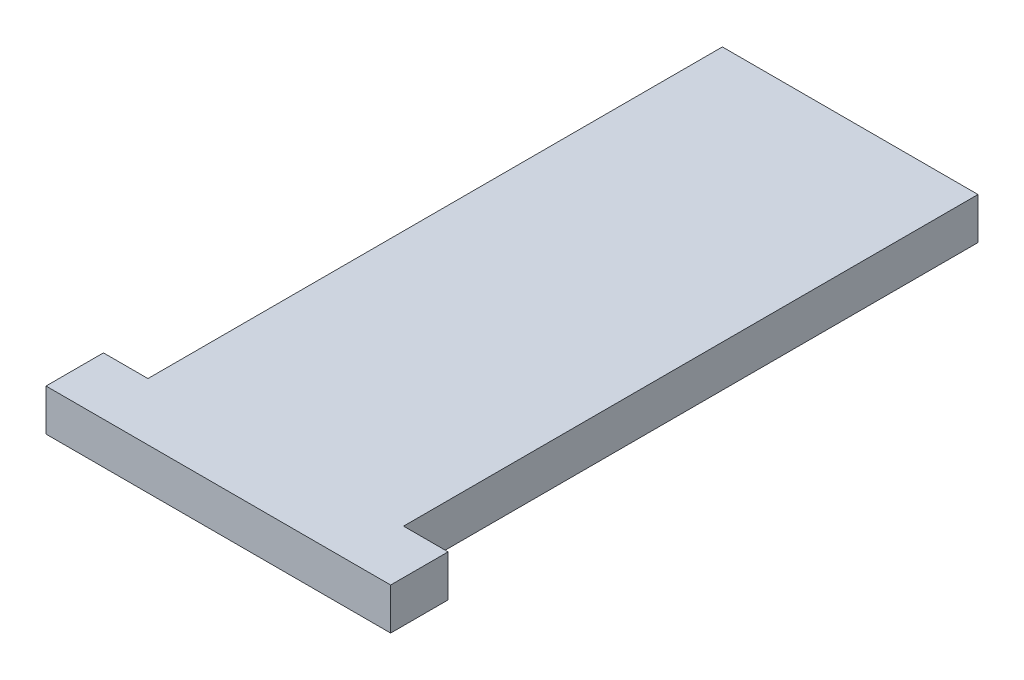
SolidWorks part; units mm, degrees
ref_plane "Front Plane" through (0, 0, 0) normal (0, 0, 1) x (1, 0, 0)
ref_plane "Top Plane" through (0, 0, 0) normal (0, 1, 0) x (1, 0, 0)
ref_plane "Right Plane" through (0, 0, 0) normal (1, 0, 0) x (0, 0, -1)
sketch "Sketch1" plane through (0, 0, 0) normal (0, 1, 0) x (1, 0, 0)
  line L0 (0, 0) -> (-30.48, 0)
  line L5 (-30.48, 0) -> (-30.48, 5.08)
  line L6 (-30.48, 5.08) -> (-26.543, 5.08)
  line L7 (-26.543, 5.08) -> (-26.543, 55.88)
  line L8 (-26.543, 55.88) -> (-3.937, 55.88)
  line L9 (-3.937, 55.88) -> (-3.937, 5.08)
  line L10 (-3.937, 5.08) -> (0, 5.08)
  line L11 (0, 5.08) -> (0, 0)
  dimension "D1" = 22.606
  dimension "D2" = 30.48
  dimension "D3" = 5.08
  dimension "D4" = 50.8
extrude "Boss-Extrude1" add sketch "Sketch1" along normal blind 3.683
